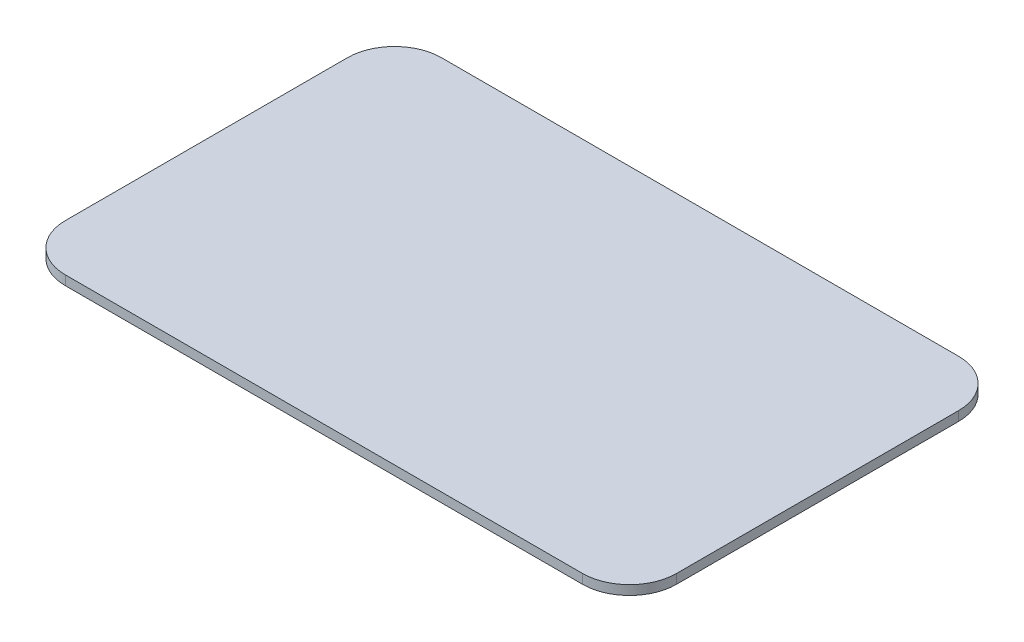
SolidWorks part; units mm, degrees
ref_plane "Front Plane" through (0, 0, 0) normal (0, 0, 1) x (1, 0, 0)
ref_plane "Top Plane" through (0, 0, 0) normal (0, 1, 0) x (1, 0, 0)
ref_plane "Right Plane" through (0, 0, 0) normal (1, 0, 0) x (0, 0, -1)
sketch "Sketch1" plane through (0, 0, 0) normal (0, 1, 0) x (1, 0, 0)
  line L0 (-54.5066, -40.3289) -> (55.4934, -40.3289)
  line L1 (65.4934, -30.3289) -> (65.4934, 29.6711)
  line L2 (-64.5066, 29.6711) -> (-64.5066, -30.3289)
  line L3 (55.4934, 39.6711) -> (-54.5066, 39.6711)
  arc A0 (-64.5066, -30.3289) -> (-54.5066, -40.3289) centre (-54.5066, -30.3289) ccw
  arc A1 (55.4934, -40.3289) -> (65.4934, -30.3289) centre (55.4934, -30.3289) ccw
  arc A2 (65.4934, 29.6711) -> (55.4934, 39.6711) centre (55.4934, 29.6711) ccw
  arc A3 (-54.5066, 39.6711) -> (-64.5066, 29.6711) centre (-54.5066, 29.6711) ccw
extrude "Boss-Extrude1" add sketch "Sketch1" along normal blind 2
